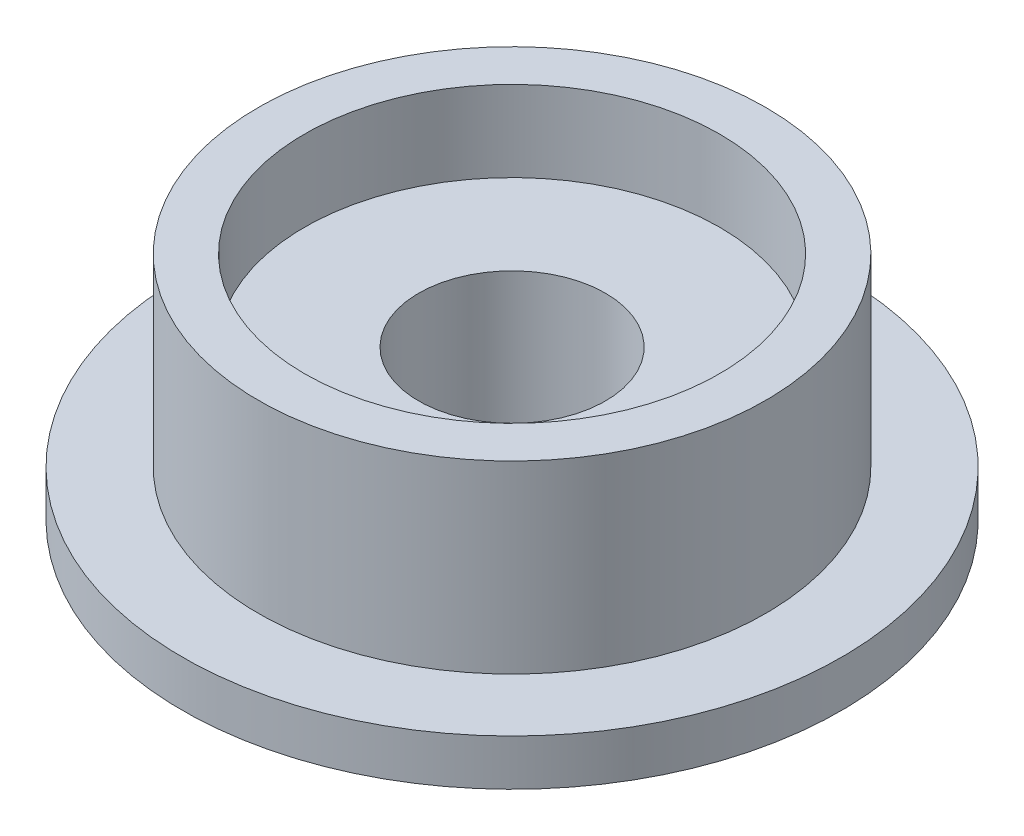
SolidWorks part; units mm, degrees
ref_plane "Front Plane" through (0, 0, 0) normal (0, 0, 1) x (1, 0, 0)
ref_plane "Top Plane" through (0, 0, 0) normal (0, 1, 0) x (1, 0, 0)
ref_plane "Right Plane" through (0, 0, 0) normal (1, 0, 0) x (0, 0, -1)
sketch "Sketch4" plane through (0, 0, 0) normal (0, 0, 1) x (1, 0, 0)
  line L0 (0, 0) -> (0, 12.0187) construction
  line L1 (4.05, 0) -> (4.05, 6.5)
  line L2 (4.05, 6.5) -> (9, 6.5)
  line L3 (9, 6.5) -> (9, 10)
  line L4 (9, 10) -> (11, 10)
  line L5 (11, 10) -> (11, 2)
  line L6 (11, 2) -> (14.2875, 2)
  line L7 (14.2875, 2) -> (14.2875, 0)
  line L8 (4.05, 0) -> (14.2875, 0)
  line L9 (0, 0) -> (4.05, 0) construction
  dimension "D1" = 28.575
  dimension "D2" = 8.1
  dimension "D3" = 18
  dimension "D4" = 22
  dimension "D5" = 6.5
  dimension "D6" = 10
  dimension "D7" = 2
  dimension "D8" = 2
revolve "Revolve1" add sketch "Sketch4" angle 360 about L0
